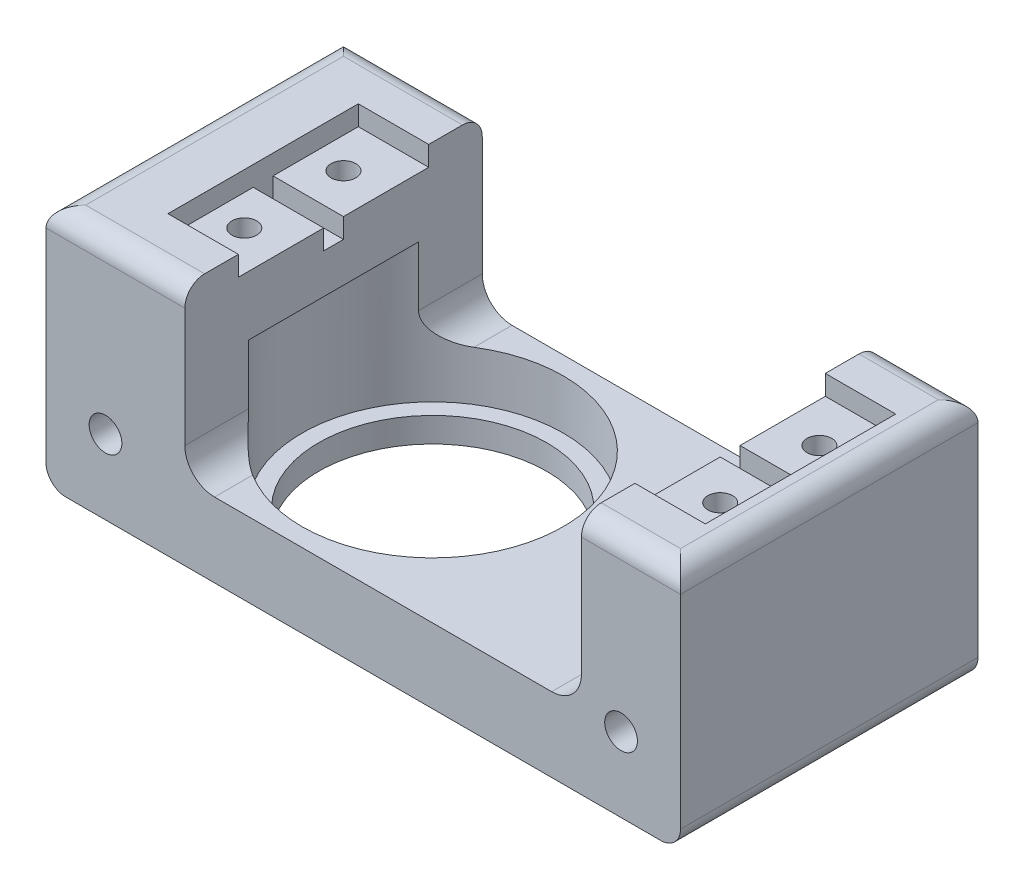
SolidWorks part; units mm, degrees
ref_plane "Спереди" through (0, 0, 0) normal (0, 0, 1) x (1, 0, 0)
ref_plane "Сверху" through (0, 0, 0) normal (0, 1, 0) x (1, 0, 0)
ref_plane "Справа" through (0, 0, 0) normal (1, 0, 0) x (0, 0, -1)
sketch "Эскиз1" plane through (0, 0, 0) normal (0, 1, 0) x (1, 0, 0)
  line L0 (0, 15) -> (0, -15) construction
  line L1 (-24, 15) -> (40, 15)
  line L2 (-24, 15) -> (-24, -15)
  line L3 (-24, -15) -> (40, -15)
  line L4 (40, 15) -> (40, -15)
  line L6 (-24, 0) -> (40, 0) construction
  point P6 (0, 0)
  dimension "D1" = 30
  dimension "D2" = 24
  dimension "D3" = 40
extrude "тело для подшипников" add sketch "Эскиз1" along normal blind 7.5
sketch "Эскиз2" plane through (0, 7.5, 0) normal (0, 1, 0) x (1, 0, 0)
  circle A0 centre (0, 0) radius 13.175
  dimension "D1" = 26.35
extrude "подшипник верхний" cut sketch "Эскиз2" against normal blind 5
sketch "Эскиз3" plane through (0, 0, 0) normal (0, -1, 0) x (1, 0, 0)
  circle A0 centre (0, 0) radius 13.175
  dimension "D1" = 26.35
extrude "подшипник нижний" [suppressed] cut sketch "Эскиз3" against normal blind 5.5
sketch "Эскиз4" plane through (0, 2.5, 0) normal (0, 1, 0) x (1, 0, 0)
  circle A0 centre (0, 0) radius 11.5
  dimension "D1" = 23
extrude "отверстие под ось" cut sketch "Эскиз4" against normal through all
sketch "Эскиз8" plane through (0, 7.5, 0) normal (0, 1, 0) x (1, 0, 0)
  line L0 (-24, 0) -> (40, 0) construction
  line L1 (-24, 15) -> (40, 15)
  line L2 (-24, 15) -> (-24, -15)
  line L3 (-24, -15) -> (40, -15)
  line L4 (40, 15) -> (40, -15)
  line L5 (-24, 15) -> (-24, -15) construction
  line L6 (0, 15) -> (0, -15) construction
  circle A0 centre (0, 0) radius 13.175
  circle A1 centre (0, 0) radius 13.175 construction
  dimension "D2" = 40
extrude "основание под сервой" add sketch "Эскиз8" along normal blind 3
sketch "Эскиз9" plane through (0, 10.5, 0) normal (0, 1, 0) x (1, 0, 0)
  line L0 (40, 15) -> (-24, 15) construction
  line L1 (-20, 15) -> (-10, 15)
  line L2 (-20, 15) -> (-20, -15)
  line L3 (-20, -15) -> (-10, -15)
  line L4 (-10, 15) -> (-10, 8.5779)
  line L5 (-24, -15) -> (40, -15) construction
  line L6 (0, 15) -> (0, -15) construction
  line L7 (40, 15) -> (30, 15)
  line L8 (40, 15) -> (40, -15)
  line L9 (40, -15) -> (30, -15)
  line L10 (30, 15) -> (30, -15)
  line L11 (-10, -8.5779) -> (-10, -15)
  arc A0 (-10, 8.5779) -> (-10, -8.5779) centre (0, 0) ccw
  circle A1 centre (0, 0) radius 13.175 construction
  dimension "D1" = 20
  dimension "D2" = 40
  dimension "D3" = 10
  dimension "D4" = 10
extrude "выступы к серве" add sketch "Эскиз9" along normal blind 12
sketch "Эскиз10" plane through (0, 22.5, 0) normal (0, 1, 0) x (1, 0, 0)
  line L0 (-20, 0) -> (40, 0) construction
  line L1 (-20, 15) -> (-20, -15) construction
  line L2 (40, -15) -> (40, 15) construction
  line L3 (-14, 5) -> (-14, -5) construction
  line L5 (34, 5) -> (34, -5) construction
  circle A0 centre (-14, 5) radius 1.25
  circle A1 centre (-14, -5) radius 1.25
  circle A2 centre (34, -5) radius 1.25
  circle A3 centre (34, 5) radius 1.25
  point P14 (34, 0)
  point P15 (-14, 0)
  dimension "D1" = 2.5
  dimension "D2" = 10
  dimension "D3" = 14
  dimension "D4" = 34
extrude "крепление сервы" cut sketch "Эскиз10" against normal blind 11
sketch "Эскиз11" plane through (0, 0, 15) normal (0, 0, 1) x (1, 0, 0)
  line L0 (-24, 7.5) -> (40, 7.5) construction
  line L2 (40, 22.5) -> (40, 0) construction
  line L4 (0, 10.5) -> (0, 0) construction
  line L5 (8, 0) -> (8, 10.5) construction
  line L6 (-10, 10.5) -> (30, 10.5) construction
  line L8 (-24, 0) -> (40, 0) construction
  circle A0 centre (-18, 7.5) radius 1.65
  circle A3 centre (34, 7.5) radius 1.65
  dimension "D1" = 3.3
  dimension "D2" = 52
  dimension "D3" = 7.5
extrude "Отверстия для шурупов" cut sketch "Эскиз11" against normal through all
mirror "Отверстия для шурупов с другой стороны" [suppressed] about plane through (0, 0, 0) normal (0, 0, 1)
sketch "Эскиз12" plane through (0, 22.5, 0) normal (0, 1, 0) x (1, 0, 0)
  line L0 (-10, -15) -> (-10, -8.5779) construction
  line L1 (-10, 8.5779) -> (-10, 15) construction
  line L2 (-20, 15) -> (-10, 15)
  line L3 (-20, 15) -> (-20, 9.6)
  line L4 (-20, 9.6) -> (-10, 9.6)
  line L5 (-20, -15) -> (-10, -15)
  line L6 (-10, 15) -> (-10, 9.6)
  line L7 (-20, -15) -> (-20, -9.6)
  line L8 (-20, -9.6) -> (-10, -9.6)
  line L9 (-10, -15) -> (-10, -9.6)
  line L10 (30, 15) -> (30, -15) construction
  line L11 (40, -15) -> (30, -15)
  line L12 (40, -15) -> (40, -9.6)
  line L13 (40, -9.6) -> (30, -9.6)
  line L14 (30, -15) -> (30, -9.6)
  line L15 (40, 15) -> (30, 15) construction
  line L16 (40, 15) -> (30, 15)
  line L17 (40, 15) -> (40, 9.6)
  line L18 (40, 9.6) -> (30, 9.6)
  line L19 (30, 15) -> (30, 9.6)
  line L20 (40, -15) -> (40, 15) construction
  dimension "D1" = 5.4
extrude "бортики к серве" add sketch "Эскиз12" along normal blind 2
sketch "Эскиз14" plane through (0, 10.5, 0) normal (0, 1, 0) x (1, 0, 0)
  line L0 (-10, 15) -> (-10, 8.5779)
  line L1 (-10, 15) -> (30, 15)
  line L2 (30, 15) -> (30, -15)
  line L3 (30, -15) -> (-10, -15)
  line L4 (-10, -15) -> (-10, -8.5779)
  arc A0 (-10, -8.5779) -> (-10, 8.5779) centre (0, 0) ccw
  arc A1 (-10, -8.5779) -> (-10, 8.5779) centre (0, 0) ccw construction
extrude "углубление впресовать подшипник" cut sketch "Эскиз14" against normal blind 3
sketch "Эскиз15" plane through (0, 22.5, 0) normal (0, 1, 0) x (1, 0, 0)
  line L1 (-20, 9.6) -> (-10, 9.6)
  line L2 (-20, 9.6) -> (-20, -9.6)
  line L3 (-20, -9.6) -> (-10, -9.6)
  line L4 (-10, 9.6) -> (-10, -9.6)
  circle A0 centre (-14, 5) radius 1.25
  circle A1 centre (-14, -5) radius 1.25
  circle A2 centre (-14, 5) radius 1.25 construction
  circle A3 centre (-14, -5) radius 1.25 construction
extrude "наплыв для саморезов" add sketch "Эскиз15" against normal blind 9
chamfer "Фаска5" distance 3 angle 45 1 edges at (-10, 13.5, 0)
sketch "Эскиз17" plane through (0, 22.5, 0) normal (0, 1, 0) x (1, 0, 0)
  line L0 (-10, -9.6) -> (-20, -9.6) construction
  line L1 (-20, 9.6) -> (-17.1, 9.6)
  line L2 (-20, 9.6) -> (-20, -9.6)
  line L3 (-20, -9.6) -> (-17.1, -9.6)
  line L4 (-17.1, 9.6) -> (-17.1, -9.6)
  line L5 (40, -9.6) -> (30, -9.6) construction
  line L6 (40, 9.6) -> (37.1, 9.6)
  line L7 (40, 9.6) -> (40, -9.6)
  line L8 (40, -9.6) -> (37.1, -9.6)
  line L9 (37.1, 9.6) -> (37.1, -9.6)
  line L10 (-20, 9.6) -> (-10, 9.6) construction
  line L11 (-20, 15) -> (-20, -15) construction
  line L12 (-20, 9.6) -> (-20, -9.6) construction
  dimension "D1" = 2.9
  dimension "D2" = 2.9
extrude "бортики к серве спереди" add sketch "Эскиз17" along normal up to surface (2 mm away) up to face at (-15, 24.5, -12.3)
sketch "Эскиз16" plane through (0, 22.5, 0) normal (0, 1, 0) x (1, 0, 0)
  line L0 (-17.1, 0) -> (37.1, 0) construction
  line L3 (-10, -9.6) -> (-10, 9.6) construction
  line L4 (-10, 1) -> (-17.1, 1)
  line L5 (-10, 1) -> (-10, -1)
  line L6 (-10, -1) -> (-17.1, -1)
  line L7 (-17.1, 1) -> (-17.1, -1)
  line L8 (30, 9.6) -> (30, -9.6) construction
  line L9 (30, -1) -> (37.1, -1)
  line L10 (30, -1) -> (30, 1)
  line L11 (30, 1) -> (37.1, 1)
  line L12 (37.1, -1) -> (37.1, 1)
  line L13 (-17.1, -9.6) -> (-17.1, 9.6) construction
  line L14 (-17.1, -9.6) -> (-17.1, 9.6) construction
  line L15 (37.1, 9.6) -> (37.1, -9.6) construction
  point P12 (-10, 0)
  point P19 (30, 0)
  dimension "D1" = 2
extrude "пазы под ребра жесткости сервы" cut sketch "Эскиз16" against normal blind 2
sketch "Эскиз18" plane through (0, 10.5, 0) normal (0, 1, 0) x (1, 0, 0)
  line L0 (-20, -15) -> (-10, -15) construction
  line L1 (-24, 15) -> (-20, 15)
  line L2 (-24, 15) -> (-24, -15)
  line L3 (-24, -15) -> (-20, -15)
  line L4 (-20, 15) -> (-20, -15)
  line L5 (-20, 15) -> (-20, -15) construction
extrude "площадка под светодиод" add sketch "Эскиз18" along normal up to surface (14 mm away) up to face at (-14.275, 24.5, 0)
fillet "Скругление4" radius 3 3 edges at (30, 7.5, 0) (-10, 7.5, -11.789) (-10, 7.5, 11.789)
fillet "Скругление5" radius 2 8 edges at (-24, 0, 0) (40, 0, 0) (35, 24.5, 15) (40, 24.5, 0) (35, 24.5, -15) (-17, 24.5, 15) (-24, 24.5, 0) (-17, 24.5, -15)
